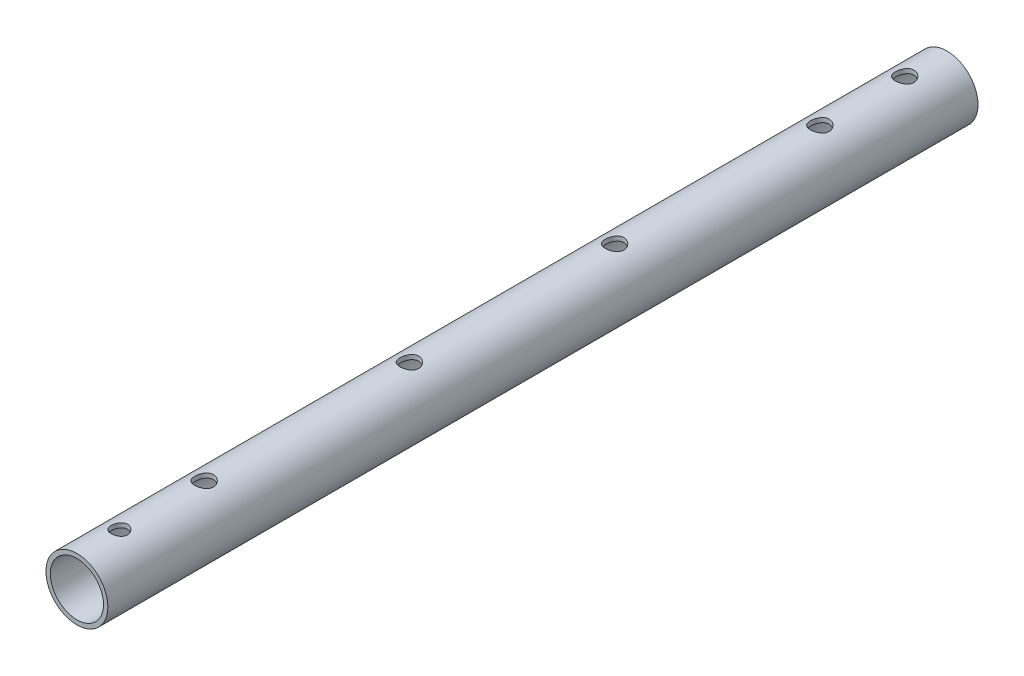
SolidWorks part; units mm, degrees
material "ASTM A36 Steel"
ref_plane "Front Plane" through (0, 0, 0) normal (0, 0, 1) x (1, 0, 0)
ref_plane "Top Plane" through (0, 0, 0) normal (0, 1, 0) x (1, 0, 0)
ref_plane "Right Plane" through (0, 0, 0) normal (1, 0, 0) x (0, 0, -1)
sketch "Sketch1" plane through (0, 0, 0) normal (0, 0, 1) x (1, 0, 0)
  circle A0 centre (0, 0) radius 36.5
  circle A2 centre (0, 0) radius 31.34
  dimension "D1" = 73
  dimension "D2" = 5.16
extrude "Boss-Extrude1" add sketch "Sketch1" along normal blind 1026
sketch "Sketch2" plane through (0, 0, 0) normal (0, 1, 0) x (1, 0, 0)
  line L0 (36.5, 0) -> (-36.5, 0) construction
  circle A0 centre (0, -50) radius 11
  circle A1 centre (0, -150) radius 11
  circle A2 centre (0, -392) radius 11
  circle A3 centre (0, -634) radius 11
  circle A4 centre (0, -876) radius 11
  circle A5 centre (0, -976) radius 9.6236
  dimension "D1" = 22
  dimension "D2" = 22
  dimension "D3" = 50
  dimension "D4" = 100
  dimension "D5" = 22
  dimension "D6" = 242
  dimension "D7" = 242
  dimension "D8" = 22
  dimension "D9" = 22
  dimension "D10" = 242
  dimension "D11" = 19.2472
  dimension "D12" = 100
extrude "Cut-Extrude1" cut sketch "Sketch2" against normal through all both and the other way through all
